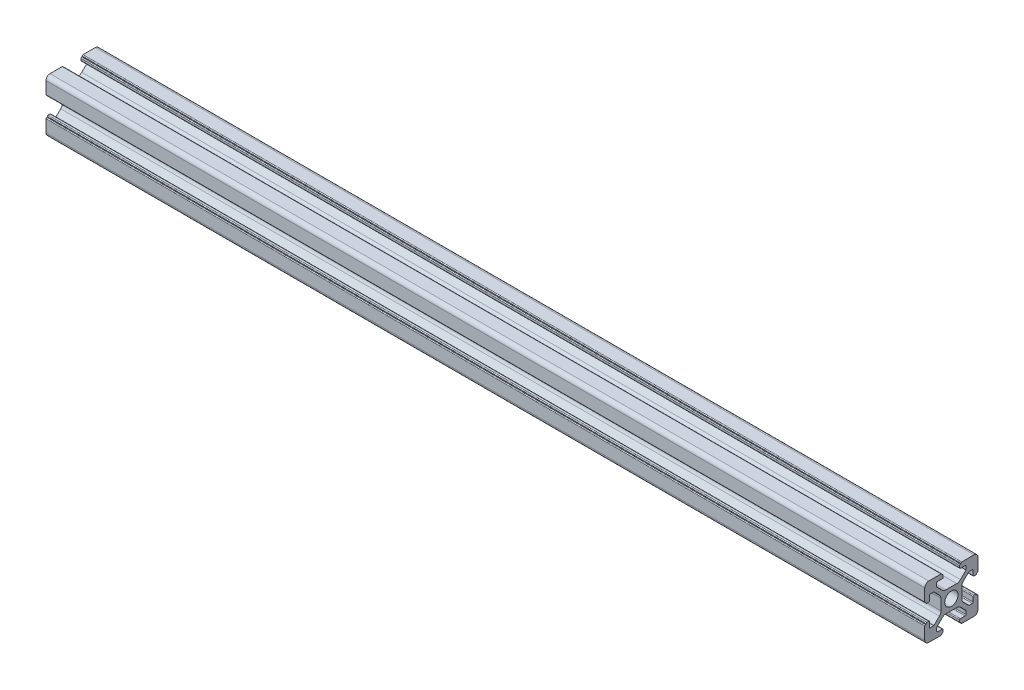
SolidWorks part; units mm, degrees
material "6061 Alloy"
ref_plane "Front Plane" through (0, 0, 0) normal (0, 0, 1) x (1, 0, 0)
ref_plane "Top Plane" through (0, 0, 0) normal (0, 1, 0) x (1, 0, 0)
ref_plane "Right Plane" through (0, 0, 0) normal (1, 0, 0) x (0, 0, -1)
sketch "Sketch1" plane through (0, 0, 0) normal (0, 0, 1) x (1, 0, 0)
  line L0 (-165, 0) -> (165, 0)
  dimension "D1" = 330
other "铝型材 2020(1)"
ref_plane "Plane1" through (-165, 0, 0) normal (1, 0, 0) x (0, 1, 0)
sketch "草图1" plane through (-165, 0, 0) normal (1, 0, 0) x (0, 1, 0)
  line L0 (3.9, 0) -> (3.9, -2.0109)
  line L1 (4.4858, -3.4251) -> (6.5607, -5.5)
  line L2 (6.5607, -5.5) -> (7.9, -5.5)
  line L3 (8.2, -5.2) -> (8.2, -3.4)
  line L4 (8.5, -3.1) -> (9.2, -3.1)
  line L5 (9.5, -3.4) -> (9.5, -3.6)
  line L6 (9.5, -3.6) -> (9.7, -3.6)
  line L7 (10, -3.9) -> (10, -8.5)
  line L8 (8.5, -10) -> (3.9, -10)
  line L9 (3.1, -9.2) -> (3.1, -8.5)
  line L10 (3.4, -8.2) -> (5.2, -8.2)
  line L11 (5.5, -7.9) -> (5.5, -6.6849)
  line L12 (5.4121, -6.4728) -> (3.4251, -4.4858)
  line L13 (2.0109, -3.9) -> (0, -3.9)
  line L14 (0, -3.9) -> (-2.0109, -3.9)
  line L15 (-3.4251, -4.4858) -> (-5.4121, -6.4728)
  line L16 (-5.5, -6.6849) -> (-5.5, -7.9)
  line L17 (-5.2, -8.2) -> (-3.4, -8.2)
  line L18 (-3.1, -8.5) -> (-3.1, -9.2)
  line L19 (-3.9, -10) -> (-8.5, -10)
  line L20 (-10, -8.5) -> (-10, -3.9)
  line L21 (-9.7, -3.6) -> (-9.5, -3.6)
  line L22 (-9.5, -3.6) -> (-9.5, -3.4)
  line L23 (-9.2, -3.1) -> (-8.5, -3.1)
  line L24 (-8.2, -3.4) -> (-8.2, -5.2)
  line L25 (-7.9, -5.5) -> (-6.6849, -5.5)
  line L26 (-6.4728, -5.4121) -> (-4.4858, -3.4251)
  line L27 (-3.9, -2.0109) -> (-3.9, 0)
  line L28 (-3.9, 0) -> (-3.9, 2.0109)
  line L29 (-4.4858, 3.4251) -> (-6.4728, 5.4121)
  line L30 (-6.6849, 5.5) -> (-7.9, 5.5)
  line L31 (-8.2, 5.2) -> (-8.2, 3.4)
  line L32 (-8.5, 3.1) -> (-9.2, 3.1)
  line L33 (-9.5, 3.4) -> (-9.5, 3.6)
  line L34 (-9.5, 3.6) -> (-9.7, 3.6)
  line L35 (-10, 3.9) -> (-10, 8.5)
  line L36 (-8.5, 10) -> (-3.9, 10)
  line L37 (-3.6, 9.7) -> (-3.6, 9.5)
  line L38 (-3.6, 9.5) -> (-3.4, 9.5)
  line L39 (-3.1, 9.2) -> (-3.1, 8.5)
  line L40 (-3.4, 8.2) -> (-5.2, 8.2)
  line L41 (-5.5, 7.9) -> (-5.5, 6.6849)
  line L42 (-5.4121, 6.4728) -> (-3.4251, 4.4858)
  line L43 (-2.0109, 3.9) -> (0, 3.9)
  line L44 (0, 3.9) -> (2.0109, 3.9)
  line L45 (3.4251, 4.4858) -> (5.4121, 6.4728)
  line L46 (5.5, 6.6849) -> (5.5, 7.9)
  line L47 (5.2, 8.2) -> (3.4, 8.2)
  line L48 (3.1, 8.5) -> (3.1, 9.2)
  line L49 (3.4, 9.5) -> (3.6, 9.5)
  line L50 (3.6, 9.5) -> (3.6, 9.7)
  line L51 (3.9, 10) -> (8.5, 10)
  line L52 (10, 8.5) -> (10, 3.9)
  line L53 (9.7, 3.6) -> (9.5, 3.6)
  line L54 (9.5, 3.6) -> (9.5, 3.4)
  line L55 (9.2, 3.1) -> (8.5, 3.1)
  line L56 (8.2, 3.4) -> (8.2, 5.2)
  line L57 (7.9, 5.5) -> (6.6849, 5.5)
  line L58 (6.4728, 5.4121) -> (4.4858, 3.4251)
  line L59 (3.9, 2.0109) -> (3.9, 0)
  circle A0 centre (0, 0) radius 2.5
  arc A1 (3.9, -2.0109) -> (4.4858, -3.4251) centre (5.9, -2.0109) ccw
  arc A2 (7.9, -5.5) -> (8.2, -5.2) centre (7.9, -5.2) ccw
  arc A3 (8.5, -3.1) -> (8.2, -3.4) centre (8.5, -3.4) ccw
  arc A4 (9.5, -3.4) -> (9.2, -3.1) centre (9.2, -3.4) ccw
  arc A5 (10, -3.9) -> (9.7, -3.6) centre (9.7, -3.9) ccw
  arc A6 (8.5, -10) -> (10, -8.5) centre (8.5, -8.5) ccw
  arc A7 (3.6, -9.7) -> (3.9, -10) centre (3.9, -9.7) ccw
  arc A8 (3.6, -9.7) -> (3.4, -9.5) centre (3.4, -9.7) ccw
  arc A9 (3.1, -9.2) -> (3.4, -9.5) centre (3.4, -9.2) ccw
  arc A10 (3.4, -8.2) -> (3.1, -8.5) centre (3.4, -8.5) ccw
  arc A11 (5.2, -8.2) -> (5.5, -7.9) centre (5.2, -7.9) ccw
  arc A12 (5.5, -6.6849) -> (5.4121, -6.4728) centre (5.2, -6.6849) ccw
  arc A13 (3.4251, -4.4858) -> (2.0109, -3.9) centre (2.0109, -5.9) ccw
  arc A14 (-2.0109, -3.9) -> (-3.4251, -4.4858) centre (-2.0109, -5.9) ccw
  arc A15 (-5.4121, -6.4728) -> (-5.5, -6.6849) centre (-5.2, -6.6849) ccw
  arc A16 (-5.5, -7.9) -> (-5.2, -8.2) centre (-5.2, -7.9) ccw
  arc A17 (-3.1, -8.5) -> (-3.4, -8.2) centre (-3.4, -8.5) ccw
  arc A18 (-3.4, -9.5) -> (-3.1, -9.2) centre (-3.4, -9.2) ccw
  arc A19 (-3.4, -9.5) -> (-3.6, -9.7) centre (-3.4, -9.7) ccw
  arc A20 (-3.9, -10) -> (-3.6, -9.7) centre (-3.9, -9.7) ccw
  arc A21 (-10, -8.5) -> (-8.5, -10) centre (-8.5, -8.5) ccw
  arc A22 (-9.7, -3.6) -> (-10, -3.9) centre (-9.7, -3.9) ccw
  arc A23 (-9.2, -3.1) -> (-9.5, -3.4) centre (-9.2, -3.4) ccw
  arc A24 (-8.2, -3.4) -> (-8.5, -3.1) centre (-8.5, -3.4) ccw
  arc A25 (-8.2, -5.2) -> (-7.9, -5.5) centre (-7.9, -5.2) ccw
  arc A26 (-6.6849, -5.5) -> (-6.4728, -5.4121) centre (-6.6849, -5.2) ccw
  arc A27 (-4.4858, -3.4251) -> (-3.9, -2.0109) centre (-5.9, -2.0109) ccw
  arc A28 (-3.9, 2.0109) -> (-4.4858, 3.4251) centre (-5.9, 2.0109) ccw
  arc A29 (-6.4728, 5.4121) -> (-6.6849, 5.5) centre (-6.6849, 5.2) ccw
  arc A30 (-7.9, 5.5) -> (-8.2, 5.2) centre (-7.9, 5.2) ccw
  arc A31 (-8.5, 3.1) -> (-8.2, 3.4) centre (-8.5, 3.4) ccw
  arc A32 (-9.5, 3.4) -> (-9.2, 3.1) centre (-9.2, 3.4) ccw
  arc A33 (-10, 3.9) -> (-9.7, 3.6) centre (-9.7, 3.9) ccw
  arc A34 (-8.5, 10) -> (-10, 8.5) centre (-8.5, 8.5) ccw
  arc A35 (-3.6, 9.7) -> (-3.9, 10) centre (-3.9, 9.7) ccw
  arc A36 (-3.1, 9.2) -> (-3.4, 9.5) centre (-3.4, 9.2) ccw
  arc A37 (-3.4, 8.2) -> (-3.1, 8.5) centre (-3.4, 8.5) ccw
  arc A38 (-5.2, 8.2) -> (-5.5, 7.9) centre (-5.2, 7.9) ccw
  arc A39 (-5.5, 6.6849) -> (-5.4121, 6.4728) centre (-5.2, 6.6849) ccw
  arc A40 (-3.4251, 4.4858) -> (-2.0109, 3.9) centre (-2.0109, 5.9) ccw
  arc A41 (2.0109, 3.9) -> (3.4251, 4.4858) centre (2.0109, 5.9) ccw
  arc A42 (5.4121, 6.4728) -> (5.5, 6.6849) centre (5.2, 6.6849) ccw
  arc A43 (5.5, 7.9) -> (5.2, 8.2) centre (5.2, 7.9) ccw
  arc A44 (3.1, 8.5) -> (3.4, 8.2) centre (3.4, 8.5) ccw
  arc A45 (3.4, 9.5) -> (3.1, 9.2) centre (3.4, 9.2) ccw
  arc A46 (3.9, 10) -> (3.6, 9.7) centre (3.9, 9.7) ccw
  arc A47 (10, 8.5) -> (8.5, 10) centre (8.5, 8.5) ccw
  arc A48 (9.7, 3.6) -> (10, 3.9) centre (9.7, 3.9) ccw
  arc A49 (9.2, 3.1) -> (9.5, 3.4) centre (9.2, 3.4) ccw
  arc A50 (8.2, 3.4) -> (8.5, 3.1) centre (8.5, 3.4) ccw
  arc A51 (8.2, 5.2) -> (7.9, 5.5) centre (7.9, 5.2) ccw
  arc A52 (6.6849, 5.5) -> (6.4728, 5.4121) centre (6.6849, 5.2) ccw
  arc A53 (4.4858, 3.4251) -> (3.9, 2.0109) centre (5.9, 2.0109) ccw
  point P0 (-10, 10)
  point P1 (10, 10)
  point P2 (10, -10)
  point P171 (-10, -10)
  point P172 (-10, 0)
  point P173 (10, 0)
  point P174 (0, -10)
  point P175 (0, 10)
  point P176 (0, 0)
  point P177 (0, 0)
